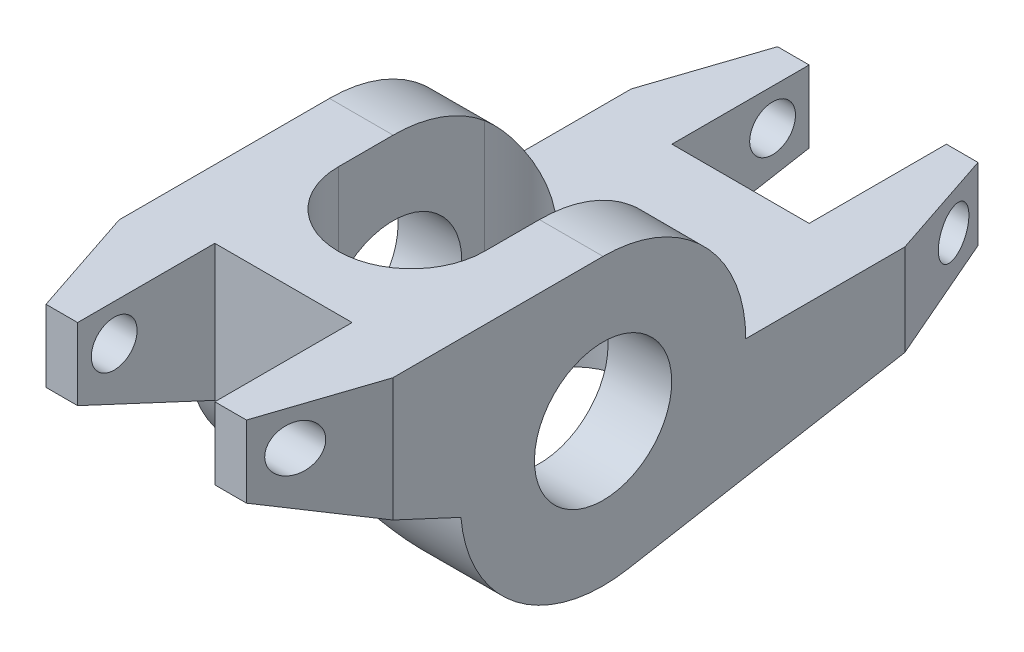
SolidWorks part; units mm, degrees
ref_plane "Front Plane" through (0, 0, 0) normal (0, 0, 1) x (1, 0, 0)
ref_plane "Top Plane" through (0, 0, 0) normal (0, 1, 0) x (1, 0, 0)
ref_plane "Right Plane" through (0, 0, 0) normal (1, 0, 0) x (0, 0, -1)
sketch "Sketch1" plane through (0, 0, 0) normal (1, 0, 0) x (0, 0, -1)
  line L0 (0, 9.9083) -> (-22.225, 9.9083)
  line L1 (-22.225, 9.9083) -> (-22.225, 4.9083)
  line L2 (-22.225, 4.9083) -> (-9.8715, -0.8523)
  line L3 (28.575, 0.0002) -> (28.575, -4.9998)
  line L4 (28.575, -4.9998) -> (1.7286, -9.7563)
  line L5 (9.9083, 0.0001) -> (28.575, 0.0002)
  circle A0 centre (0, 0) radius 4.765
  arc A1 (-9.8715, -0.8523) -> (1.7286, -9.7563) centre (0, 0) ccw
  arc A2 (9.9083, 0.0001) -> (0, 9.9083) centre (0, 0) ccw
  dimension "D1" = 22.225
  dimension "D2" = 5
  dimension "D3" = 13.6305
  dimension "D4" = 25
  dimension "D5" = 5
  dimension "D6" = 27.2645
  dimension "D8" = 28.575
extrude "Boss-Extrude1" add sketch "Sketch1" along normal mid plane 19
chamfer "Chamfer1" distance 2.54 distance2 7.62 2 edges at (9.5, -2.4998, -28.575) (9.5, 7.4083, 22.225)
chamfer "Chamfer3" distance 7.62 distance2 2.54 2 edges at (-9.5, -2.4998, -28.575) (-9.5, 7.4083, 22.225)
sketch "Sketch2" plane through (0, 0, 0) normal (0, 1, 0) x (1, 0, 0)
  line L0 (0, -3.81) -> (0, 6.35) construction
  line L1 (-5.08, -3.81) -> (-5.08, 6.35)
  line L2 (5.08, -3.81) -> (5.08, 6.35)
  arc A0 (-5.08, -3.81) -> (5.08, -3.81) centre (0, -3.81) ccw
  arc A1 (5.08, 6.35) -> (-5.08, 6.35) centre (0, 6.35) ccw
  point P3 (0, 1.27)
  dimension "D1" = 10.16
  dimension "D2" = 10.16
  dimension "D3" = 3.81
extrude "Cut-Extrude2" cut sketch "Sketch2" against normal through all both and the other way through all
sketch "Sketch3" plane through (0, 0, 0) normal (0, 1, 0) x (1, 0, 0)
  line L0 (-4.765, -22.2249) -> (-4.765, -26.2883)
  line L5 (-4.765, -26.2883) -> (4.765, -26.2883)
  line L10 (6.96, 28.575) -> (-6.96, 28.575) construction
  line L11 (-4.765, 19.045) -> (4.765, 19.045)
  line L12 (-4.765, 19.045) -> (-4.765, 28.575)
  line L13 (-4.765, 28.575) -> (4.765, 28.575)
  line L14 (4.765, 19.045) -> (4.765, 28.575)
  line L15 (-4.765, 19.045) -> (4.765, 28.575) construction
  line L16 (-4.765, 28.575) -> (4.765, 19.045) construction
  line L17 (6.96, -22.2249) -> (-6.96, -22.2249) construction
  line L18 (4.765, -12.6949) -> (-4.765, -12.6949)
  line L19 (4.765, -12.6949) -> (4.765, -22.2249)
  line L21 (-4.765, -12.6949) -> (-4.765, -22.2249)
  line L22 (4.765, -12.6949) -> (-4.765, -22.2249) construction
  line L23 (4.765, -22.2249) -> (-4.765, -12.6949) construction
  line L24 (4.765, -26.2883) -> (4.765, -22.2249)
  point P0 (0, 23.81)
  point P7 (0, -17.4599)
  dimension "D1" = 9.53
  dimension "D2" = 4.0634
  dimension "D3" = 9.53
  dimension "D4" = 9.53
  dimension "D5" = 9.53
  dimension "D6" = 4.0634
extrude "Cut-Extrude5" cut sketch "Sketch3" against normal mid plane 100
sketch "Sketch4" plane through (0, 0, 0) normal (1, 0, 0) x (0, 0, -1)
  line L0 (20.955, 0.0001) -> (28.575, 0.0002) construction
  line L1 (28.575, 0.0002) -> (28.575, -4.9998) construction
  line L2 (-22.225, 9.9083) -> (-14.605, 9.9083) construction
  line L3 (-22.225, 4.9083) -> (-22.225, 9.9083) construction
  circle A0 centre (26.035, -2.5398) radius 1.59
  circle A1 centre (-19.685, 7.3683) radius 1.59
  dimension "D1" = 3.18
  dimension "D2" = 2.54
  dimension "D4" = 2.54
  dimension "D5" = 2.54
  dimension "D6" = 3.18
  dimension "D3" = 2.54
extrude "Cut-Extrude6" cut sketch "Sketch4" against normal mid plane 100
